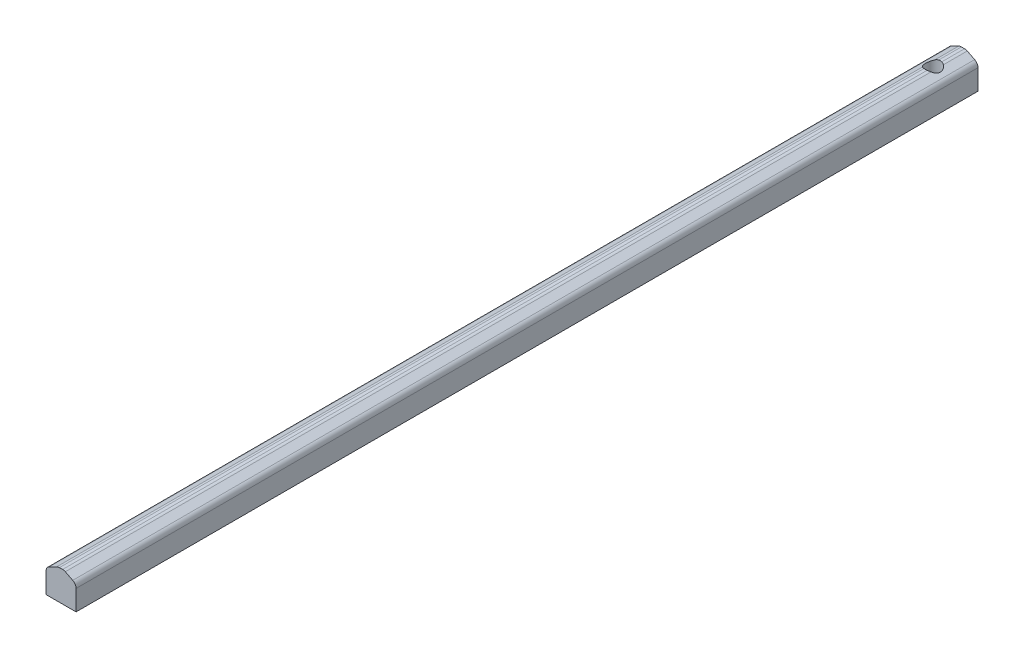
SolidWorks part; units mm, degrees
ref_plane "Plan de face" through (0, 0, 0) normal (0, 0, 1) x (1, 0, 0)
ref_plane "Plan de dessus" through (0, 0, 0) normal (0, 1, 0) x (1, 0, 0)
ref_plane "Plan de droite" through (0, 0, 0) normal (1, 0, 0) x (0, 0, -1)
sketch "Esquisse1" plane through (0, 0, 0) normal (0, 0, 1) x (1, 0, 0)
  line L1 (0, 0) -> (10, 0)
  line L2 (0, 0) -> (0, 10)
  line L3 (0, 10) -> (10, 10)
  line L4 (10, 0) -> (10, 10)
  dimension "D1" = 10
  dimension "D2" = 10
extrude "Boss.-Extru.1" add sketch "Esquisse1" along normal blind 300
sketch "Esquisse2" plane through (0, 10, 0) normal (0, 1, 0) x (1, 0, 0)
  line L0 (10, 0) -> (0, 0) construction
  line L1 (10, -300) -> (10, 0) construction
  circle A0 centre (5, -10) radius 2.5
  dimension "D1" = 5
  dimension "D2" = 10
  dimension "D3" = 5
extrude "Enlèv. mat.-Extru.1" cut sketch "Esquisse2" against normal through all contours A0
sketch "Esquisse3" plane through (0, 0, 0) normal (0, 0, -1) x (-1, 0, 0)
  line L0 (0, 10) -> (0, 8)
  line L3 (0, 10) -> (0, 0) construction
  line L5 (0, 10) -> (-4, 10)
  line L6 (-10, 10) -> (0, 10) construction
  line L7 (-4, 10) -> (0, 8)
  line L8 (-10, 10) -> (-10, 8)
  line L9 (-10, 0) -> (-10, 10) construction
  line L10 (-10, 8) -> (-6, 10)
  line L11 (-10, 10) -> (0, 10) construction
  line L12 (-6, 10) -> (-10, 10)
  dimension "D1" = 2
  dimension "D2" = 4
  dimension "D3" = 4
  dimension "D4" = 2
extrude "Enlèv. mat.-Extru.2" cut sketch "Esquisse3" against normal through all
fillet "Congé2" radius 2 2 edges at (6, 10, 156.1456) (4, 10, 156.1456)
fillet "Congé3" radius 2 2 edges at (10, 8, 150) (0, 8, 150)
fillet "Congé4" radius 2 2 edges at (6, 10, 3.8544) (4, 10, 3.8544)
